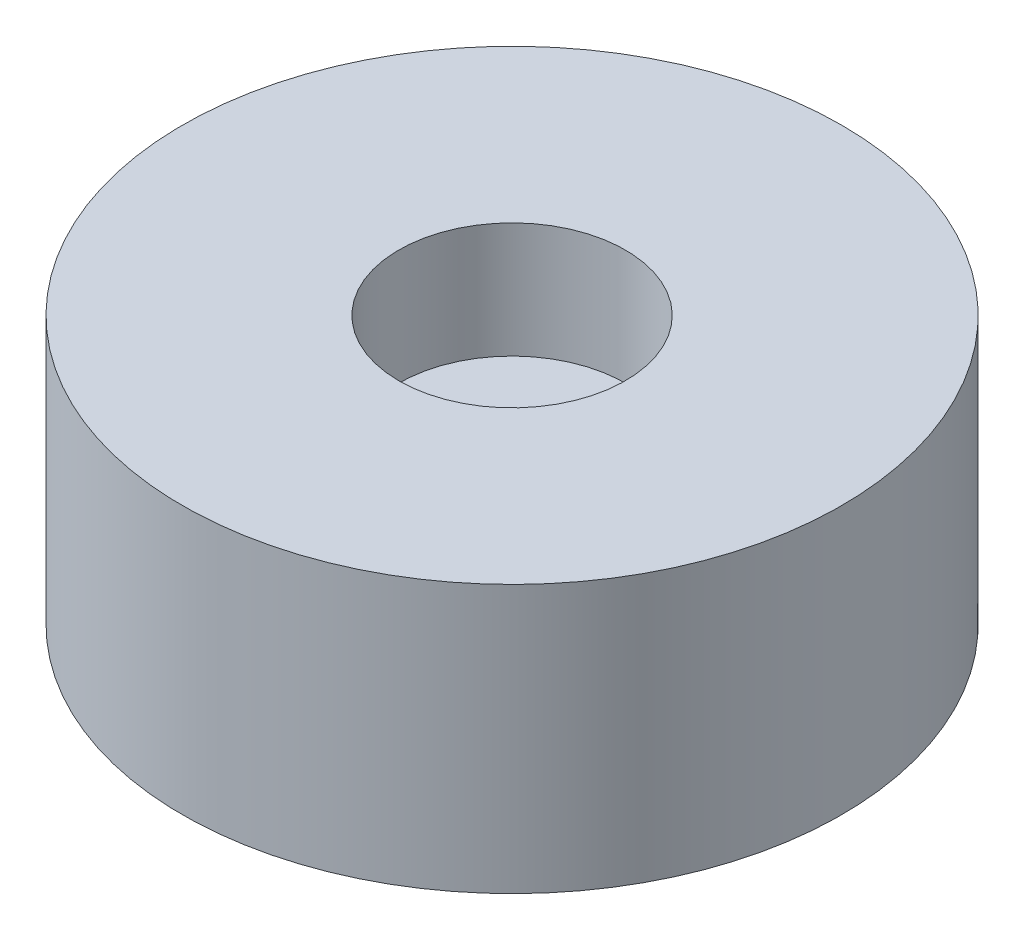
SolidWorks part; units mm, degrees
ref_plane "Front Plane" through (0, 0, 0) normal (0, 0, 1) x (1, 0, 0)
ref_plane "Top Plane" through (0, 0, 0) normal (0, 1, 0) x (1, 0, 0)
ref_plane "Right Plane" through (0, 0, 0) normal (1, 0, 0) x (0, 0, -1)
sketch "Sketch1" plane through (0, 0, 0) normal (0, 1, 0) x (1, 0, 0)
  circle A0 centre (0, 0) radius 8
  dimension "D1" = 16
extrude "Boss-Extrude1" add sketch "Sketch1" along normal blind 6.5
sketch "Sketch2" plane through (0, 6.5, 0) normal (0, 1, 0) x (1, 0, 0)
  circle A0 centre (0, 0) radius 2.75
  dimension "D1" = 5.5
extrude "Cut-Extrude1" cut sketch "Sketch2" against normal blind 2.8
sketch "Sketch3" plane through (0, 0, 0) normal (0, -1, 0) x (1, 0, 0)
  circle A0 centre (0, 0) radius 1.5
  dimension "D1" = 3
extrude "Boss-Extrude2" add sketch "Sketch3" along normal blind 2
